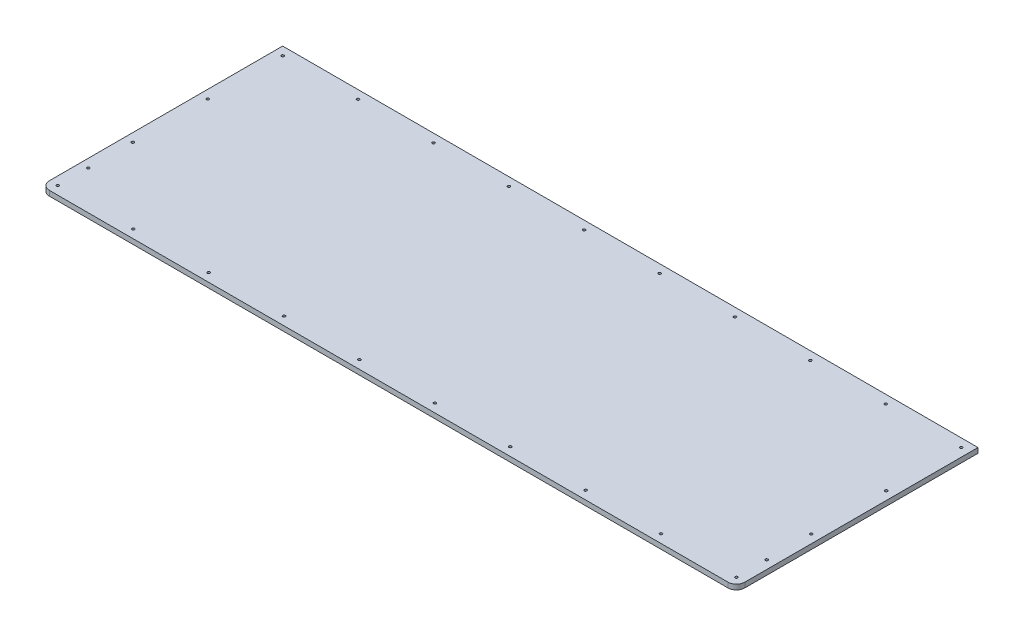
SolidWorks part; units mm, degrees
ref_plane "Płaszczyzna przednia" through (0, 0, 0) normal (0, 0, 1) x (1, 0, 0)
ref_plane "Płaszczyzna górna" through (0, 0, 0) normal (0, 1, 0) x (1, 0, 0)
ref_plane "Płaszczyzna prawa" through (0, 0, 0) normal (1, 0, 0) x (0, 0, -1)
sketch "Szkic2" plane through (0, 1505.9474, 0) normal (0, 1, 0) x (0, 0, 1)
  line L0 (-189.9552, 667.685) -> (-189.9552, -158.315)
  line L1 (-189.9552, 667.685) -> (87.0448, 667.685)
  line L2 (-189.9552, -158.315) -> (87.0448, -158.315)
  line L3 (97.0448, 657.685) -> (97.0448, -148.315)
  arc A0 (87.0448, -158.315) -> (97.0448, -148.315) centre (87.0448, -148.315) ccw
  arc A1 (87.0448, 667.685) -> (97.0448, 657.685) centre (87.0448, 657.685) cw
  dimension "D3" = 10
  dimension "D1" = 826
  dimension "D2" = 287
extrude "Dodanie-wyciągnięcie1" add sketch "Szkic2" along normal blind 6
sketch "Szkic3" plane through (0, 1505.9474, 0) normal (0, -1, 0) x (1, 0, 0)
  circle A3 centre (-148.315, 87.0448) radius 1.55
  circle A4 centre (-148.315, 87.0448) radius 1.55
  dimension "D2" = 0
extrude "Wytnij-wyciągnięcie1" cut sketch "Szkic3" against normal blind 6
pattern_linear "Szyk liniowy1" count 2 spacing 36 along (0, 0, -1) count 4 spacing 89 along (0, 0, -1) of "Wytnij-wyciągnięcie1"
pattern_linear "Szyk liniowy2" count 9 spacing 89.555 along (1, 0, 0) of "Wytnij-wyciągnięcie1"
sketch "Szkic4" plane through (0, 1505.9474, 0) normal (0, -1, 0) x (1, 0, 0)
  circle A0 centre (657.685, -179.9552) radius 1.55 construction
  circle A1 centre (657.685, -179.9552) radius 1.55
extrude "Wytnij-wyciągnięcie2" cut sketch "Szkic4" against normal blind 6
pattern_linear "Szyk liniowy3" count 9 spacing 89.555 along (-1, 0, 0) count 4 spacing 89 along (0, 0, 1) of "Wytnij-wyciągnięcie2"
pattern_linear "Szyk liniowy4" count 2 spacing 231 along (0, 0, 1) of "Wytnij-wyciągnięcie2"
